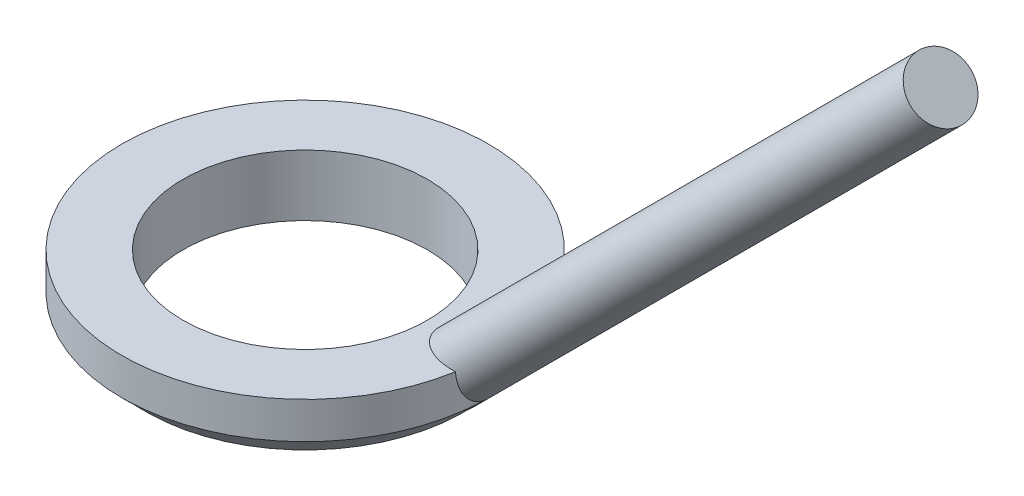
SolidWorks part; units mm, degrees
ref_plane "Front Plane" through (0, 0, 0) normal (0, 0, 1) x (1, 0, 0)
ref_plane "Top Plane" through (0, 0, 0) normal (0, 1, 0) x (1, 0, 0)
ref_plane "Right Plane" through (0, 0, 0) normal (1, 0, 0) x (0, 0, -1)
sketch "Sketch1" plane through (0, 0, 0) normal (0, 0, 1) x (1, 0, 0)
  line L0 (0, 0) -> (0, 42.3664) construction
  line L2 (12.7, 0) -> (19.05, 0)
  line L3 (12.7, 0) -> (12.7, 6.35)
  line L4 (12.7, 6.35) -> (19.05, 6.35)
  line L5 (19.05, 0) -> (19.05, 6.35)
  dimension "D1" = 6.35
  dimension "D2" = 6.35
  dimension "D3" = 25.4
revolve "Revolve1" add sketch "Sketch1" angle 360 about L0
chamfer "Chamfer1" distance 2.54 angle 45 1 edges at (0, 0, -19.05)
sketch "Sketch2" plane through (0, 0, 0) normal (0, 0, 1) x (1, 0, 0)
  line L0 (15.24, 3.175) -> (75.8675, 63.8025) construction
  line L1 (15.24, 3.175) -> (66.04, 53.975)
  line L2 (15.24, 3.175) -> (12.9949, 5.4201)
  line L3 (66.04, 53.975) -> (63.7949, 56.2201)
  line L4 (12.9949, 5.4201) -> (63.7949, 56.2201)
  line L5 (19.05, 6.35) -> (-19.05, 6.35) construction
  line L6 (0, 0) -> (15.24, 0) construction
  line L7 (-16.51, 0) -> (16.51, 0) construction
  line L8 (15.24, 0) -> (15.24, 3.175) construction
  dimension "D1" = 135
  dimension "D2" = 6.35
  dimension "D3" = 3.175
  dimension "D4" = 15.24
  dimension "D5" = 50.8
revolve "Revolve2" add sketch "Sketch2" angle 360 about L0
